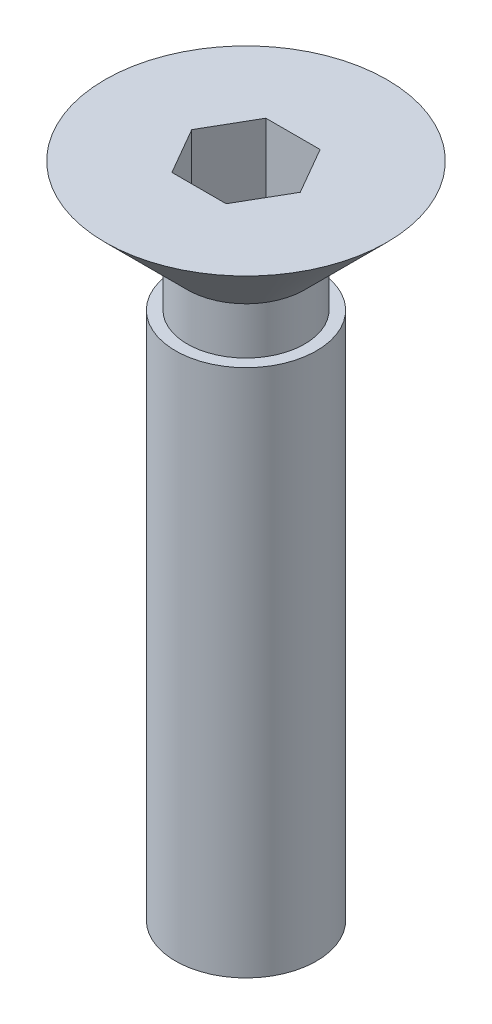
SolidWorks part; units mm, degrees
material "AISI 304"
ref_plane "前视基准面" through (0, 0, 0) normal (0, 0, 1) x (1, 0, 0)
ref_plane "上视基准面" through (0, 0, 0) normal (0, 1, 0) x (1, 0, 0)
ref_plane "右视基准面" through (0, 0, 0) normal (1, 0, 0) x (0, 0, -1)
sketch "草图1" plane through (0, 0, 0) normal (0, 0, 1) x (1, 0, 0)
  line L0 (0, 0) -> (0, 14) construction
  line L1 (0, 14) -> (-3, 14)
  line L2 (-3, 14) -> (-1.25, 12.25)
  line L3 (-1.25, 12.25) -> (-1.25, 11.25)
  line L4 (-1.25, 11.25) -> (-1.5, 11.25)
  line L5 (-1.5, 11.25) -> (-1.5, 0)
  line L6 (-1.5, 0) -> (0, 0)
  line L7 (0, 0) -> (0, 14)
  dimension "D1" = 6
  dimension "D2" = 45
  dimension "D3" = 3
  dimension "D4" = 14
  dimension "D5" = 1
  dimension "D6" = 2.5
revolve "旋转1" add sketch "草图1" angle 360 about L0
cosmetic thread "装饰螺纹线1" parameters "D2"=2.439
sketch "草图2" plane through (0, 14, 0) normal (0, 1, 0) x (1, 0, 0)
  line L1 (0.5774, 1) -> (-0.5774, 1)
  line L2 (-0.5774, 1) -> (-1.1547, 0)
  line L3 (-1.1547, 0) -> (-0.5774, -1)
  line L4 (-0.5774, -1) -> (0.5774, -1)
  line L5 (0.5774, -1) -> (1.1547, 0)
  line L6 (1.1547, 0) -> (0.5774, 1)
  circle A0 centre (0, 0) radius 1 construction
  dimension "D1" = 2
extrude "切除-拉伸1" cut sketch "草图2" against normal blind 2
